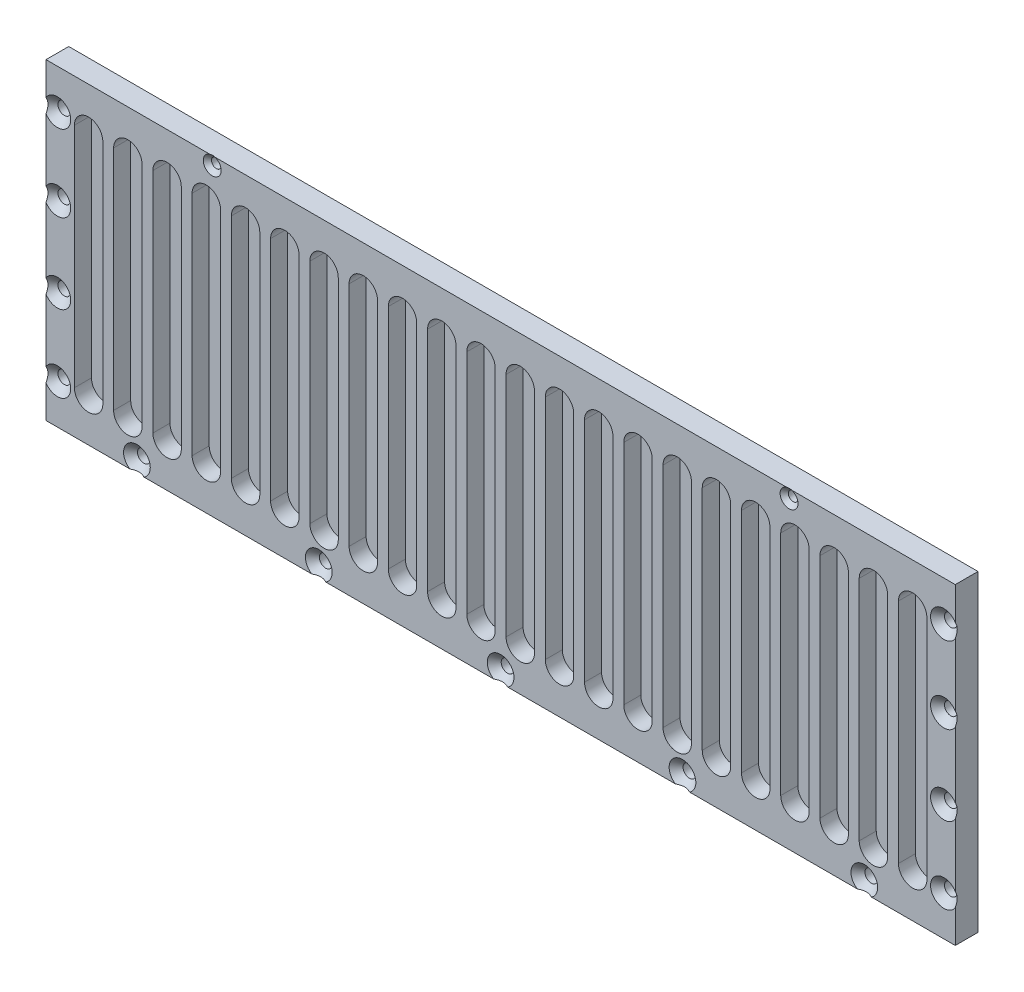
SolidWorks part; units mm, degrees
material "7079 Alloy"
ref_plane "Front Plane" through (0, 0, 0) normal (0, 0, 1) x (1, 0, 0)
ref_plane "Top Plane" through (0, 0, 0) normal (0, 1, 0) x (1, 0, 0)
ref_plane "Right Plane" through (0, 0, 0) normal (1, 0, 0) x (0, 0, -1)
sketch "Sketch1" plane through (0, 0, 0) normal (0, 0, 1) x (1, 0, 0)
  line L0 (-160, 0) -> (0, 0) construction
  line L1 (-160, 55) -> (160, 55)
  line L2 (-160, 55) -> (-160, -55)
  line L3 (-160, -55) -> (160, -55)
  line L4 (160, 55) -> (160, -55)
  line L5 (0, 0) -> (0, 55) construction
  dimension "D1" = 110
  dimension "D2" = 320
extrude "Extrude1" add sketch "Sketch1" along normal blind 8
sketch "Sketch2" plane through (0, 0, 8) normal (0, 0, 1) x (1, 0, 0)
  line L0 (156, 55) -> (156, -55) construction
  line L1 (160, 55) -> (-160, 55) construction
  line L2 (-160, -55) -> (160, -55) construction
  line L3 (0, 55) -> (0, -55) construction
  line L4 (160, 0) -> (0, 0) construction
  line L5 (160, -55) -> (160, 55) construction
  circle A0 centre (156, 41) radius 1.75
  circle A1 centre (156, 14) radius 1.75
  circle A2 centre (156, -14) radius 1.75
  circle A3 centre (156, -41) radius 1.75
  circle A4 centre (-156, -41) radius 1.75
  circle A5 centre (-156, -14) radius 1.75
  circle A6 centre (-156, 41) radius 1.75
  circle A7 centre (-156, 14) radius 1.75
  dimension "D1" = 3.5
  dimension "D2" = 14
  dimension "D3" = 27
  dimension "D4" = 4
extrude "Cut-Extrude1" cut sketch "Sketch2" against normal through all
sketch "Sketch5" plane through (0, 0, 8) normal (0, 0, 1) x (1, 0, 0)
  line L0 (145, 0) -> (145, 55) construction
  line L1 (-160, 55) -> (-160, -55) construction
  line L2 (145, 0) -> (160, 0) construction
  line L3 (160, -55) -> (160, 55) construction
  line L4 (150, 40) -> (150, -40)
  line L5 (140, 40) -> (140, -40)
  line L7 (160, 55) -> (-160, 55) construction
  line L37 (136.1905, 40) -> (136.1905, -40)
  line L38 (126.1905, 40) -> (126.1905, -40)
  line L39 (122.381, 40) -> (122.381, -40)
  line L40 (112.381, 40) -> (112.381, -40)
  line L41 (108.5714, 40) -> (108.5714, -40)
  line L42 (98.5714, 40) -> (98.5714, -40)
  line L43 (94.7619, 40) -> (94.7619, -40)
  line L44 (84.7619, 40) -> (84.7619, -40)
  line L45 (80.9524, 40) -> (80.9524, -40)
  line L46 (70.9524, 40) -> (70.9524, -40)
  line L47 (67.1429, 40) -> (67.1429, -40)
  line L48 (57.1429, 40) -> (57.1429, -40)
  line L49 (53.3333, 40) -> (53.3333, -40)
  line L50 (43.3333, 40) -> (43.3333, -40)
  line L51 (39.5238, 40) -> (39.5238, -40)
  line L52 (29.5238, 40) -> (29.5238, -40)
  line L53 (25.7143, 40) -> (25.7143, -40)
  line L54 (15.7143, 40) -> (15.7143, -40)
  line L55 (11.9048, 40) -> (11.9048, -40)
  line L56 (1.9048, 40) -> (1.9048, -40)
  line L57 (-1.9048, 40) -> (-1.9048, -40)
  line L58 (-11.9048, 40) -> (-11.9048, -40)
  line L59 (-15.7143, 40) -> (-15.7143, -40)
  line L60 (-25.7143, 40) -> (-25.7143, -40)
  line L61 (-29.5238, 40) -> (-29.5238, -40)
  line L62 (-39.5238, 40) -> (-39.5238, -40)
  line L63 (-43.3333, 40) -> (-43.3333, -40)
  line L64 (-53.3333, 40) -> (-53.3333, -40)
  line L65 (-57.1429, 40) -> (-57.1429, -40)
  line L66 (-67.1429, 40) -> (-67.1429, -40)
  line L67 (-70.9524, 40) -> (-70.9524, -40)
  line L68 (-80.9524, 40) -> (-80.9524, -40)
  line L69 (-84.7619, 40) -> (-84.7619, -40)
  line L70 (-94.7619, 40) -> (-94.7619, -40)
  line L71 (-98.5714, 40) -> (-98.5714, -40)
  line L72 (-108.5714, 40) -> (-108.5714, -40)
  line L93 (-112.381, 40) -> (-112.381, -40)
  line L94 (-122.381, 40) -> (-122.381, -40)
  line L95 (-126.1905, 40) -> (-126.1905, -40)
  line L96 (-136.1905, 40) -> (-136.1905, -40)
  line L97 (-140, 40) -> (-140, -40)
  line L98 (-150, 40) -> (-150, -40)
  arc A0 (150, 40) -> (140, 40) centre (145, 40) ccw
  arc A1 (150, -40) -> (140, -40) centre (145, -40) cw
  arc A30 (136.1905, 40) -> (126.1905, 40) centre (131.1905, 40) ccw
  arc A31 (136.1905, -40) -> (126.1905, -40) centre (131.1905, -40) cw
  arc A32 (122.381, 40) -> (112.381, 40) centre (117.381, 40) ccw
  arc A33 (122.381, -40) -> (112.381, -40) centre (117.381, -40) cw
  arc A34 (108.5714, 40) -> (98.5714, 40) centre (103.5714, 40) ccw
  arc A35 (108.5714, -40) -> (98.5714, -40) centre (103.5714, -40) cw
  arc A36 (94.7619, 40) -> (84.7619, 40) centre (89.7619, 40) ccw
  arc A37 (94.7619, -40) -> (84.7619, -40) centre (89.7619, -40) cw
  arc A38 (80.9524, 40) -> (70.9524, 40) centre (75.9524, 40) ccw
  arc A39 (80.9524, -40) -> (70.9524, -40) centre (75.9524, -40) cw
  arc A40 (67.1429, 40) -> (57.1429, 40) centre (62.1429, 40) ccw
  arc A41 (67.1429, -40) -> (57.1429, -40) centre (62.1429, -40) cw
  arc A42 (53.3333, 40) -> (43.3333, 40) centre (48.3333, 40) ccw
  arc A43 (53.3333, -40) -> (43.3333, -40) centre (48.3333, -40) cw
  arc A44 (39.5238, 40) -> (29.5238, 40) centre (34.5238, 40) ccw
  arc A45 (39.5238, -40) -> (29.5238, -40) centre (34.5238, -40) cw
  arc A46 (25.7143, 40) -> (15.7143, 40) centre (20.7143, 40) ccw
  arc A47 (25.7143, -40) -> (15.7143, -40) centre (20.7143, -40) cw
  arc A48 (11.9048, 40) -> (1.9048, 40) centre (6.9048, 40) ccw
  arc A49 (11.9048, -40) -> (1.9048, -40) centre (6.9048, -40) cw
  arc A50 (-1.9048, 40) -> (-11.9048, 40) centre (-6.9048, 40) ccw
  arc A51 (-1.9048, -40) -> (-11.9048, -40) centre (-6.9048, -40) cw
  arc A52 (-15.7143, 40) -> (-25.7143, 40) centre (-20.7143, 40) ccw
  arc A53 (-15.7143, -40) -> (-25.7143, -40) centre (-20.7143, -40) cw
  arc A54 (-29.5238, 40) -> (-39.5238, 40) centre (-34.5238, 40) ccw
  arc A55 (-29.5238, -40) -> (-39.5238, -40) centre (-34.5238, -40) cw
  arc A56 (-43.3333, 40) -> (-53.3333, 40) centre (-48.3333, 40) ccw
  arc A57 (-43.3333, -40) -> (-53.3333, -40) centre (-48.3333, -40) cw
  arc A58 (-57.1429, 40) -> (-67.1429, 40) centre (-62.1429, 40) ccw
  arc A59 (-57.1429, -40) -> (-67.1429, -40) centre (-62.1429, -40) cw
  arc A60 (-70.9524, 40) -> (-80.9524, 40) centre (-75.9524, 40) ccw
  arc A61 (-70.9524, -40) -> (-80.9524, -40) centre (-75.9524, -40) cw
  arc A62 (-84.7619, 40) -> (-94.7619, 40) centre (-89.7619, 40) ccw
  arc A63 (-84.7619, -40) -> (-94.7619, -40) centre (-89.7619, -40) cw
  arc A64 (-98.5714, 40) -> (-108.5714, 40) centre (-103.5714, 40) ccw
  arc A65 (-98.5714, -40) -> (-108.5714, -40) centre (-103.5714, -40) cw
  arc A66 (-112.381, 40) -> (-122.381, 40) centre (-117.381, 40) ccw
  arc A67 (-112.381, -40) -> (-122.381, -40) centre (-117.381, -40) cw
  arc A90 (-126.1905, 40) -> (-136.1905, 40) centre (-131.1905, 40) ccw
  arc A91 (-126.1905, -40) -> (-136.1905, -40) centre (-131.1905, -40) cw
  arc A92 (-140, 40) -> (-150, 40) centre (-145, 40) ccw
  arc A93 (-140, -40) -> (-150, -40) centre (-145, -40) cw
  point P11 (150, 0)
  point P16 (140, 0)
  dimension "D1" = 80
  dimension "D2" = 5
  dimension "D3" = 15
  dimension "D5" = 15
  dimension "D4" = 22
extrude "Cut-Extrude2" cut sketch "Sketch5" against normal blind 6
sketch "Sketch6" plane through (0, 0, 8) normal (0, 0, 1) x (1, 0, 0)
  line L0 (-152, -55) -> (-152, -51) construction
  line L1 (-160, -55) -> (160, -55) construction
  line L2 (-152, -51) -> (0, -51) construction
  line L3 (0, -51) -> (0, -55) construction
  line L4 (-160, 55) -> (-160, -55) construction
  circle A0 centre (-64, -51) radius 2.25
  circle A1 centre (0, -51) radius 2.25
  circle A2 centre (64, -51) radius 2.25
  circle A3 centre (-128, -51) radius 2.25
  circle A4 centre (128, -51) radius 2.25
  dimension "D2" = 5
  dimension "D3" = 4.5
  dimension "D4" = 8
  dimension "D5" = 4
  dimension "D1" = 64
extrude "Cut-Extrude3" cut sketch "Sketch6" against normal blind 10
sketch "Sketch9" plane through (0, 0, 8) normal (0, 0, 1) x (1, 0, 0)
  line L0 (160, 52) -> (101.5, 52) construction
  line L1 (160, -55) -> (160, 55) construction
  line L2 (101.5, 52) -> (101.5, 55) construction
  line L3 (160, 55) -> (-160, 55) construction
  line L4 (0, 0) -> (0, 55) construction
  circle A0 centre (101.5, 52) radius 1.5
  circle A1 centre (-101.5, 52) radius 1.5
  dimension "D1" = 3
  dimension "D2" = 3
  dimension "D3" = 58.5
extrude "Cut-Extrude4" cut sketch "Sketch9" against normal blind 10
hole_wizard "CSK for M4 Flat Head Machine Screw1" positions "Sketch4" profile "Sketch3" countersink size "M4" standard "Ansi Metric" end condition through all
sketch "Sketch4" plane through (0, 0, 8) normal (0, 0, 1) x (1, 0, 0)
  point P1 (156, 41)
  point P4 (156, 14)
  point P7 (156, -14)
  point P10 (156, -41)
  point P13 (-156, -41)
  point P16 (-156, -14)
  point P19 (-156, 14)
  point P26 (-156, 41)
  point P35 (-128, -51)
  point P38 (-64, -51)
  point P41 (0, -51)
  point P44 (64, -51)
  point P47 (128, -51)
sketch "Sketch3" plane through (156, 41, 8) normal (1, 0, 0) x (0, -1, 0)
  line L0 (0, 0) -> (0, 8)
  line L1 (0, 8) -> (2.25, 8)
  line L2 (2.25, 8) -> (2.25, 2.45)
  line L3 (2.25, 2.45) -> (4.7, 0)
  line L5 (4.7, 0) -> (0, 0)
  line L6 (-2.25, 2.45) -> (-4.7, 0) construction
  line L11 (0, -6.35) -> (0, 107.95) construction
  dimension "Thru Hole Dia." = 4.5
  dimension "Thru Hole Depth" = 8
  dimension "Near C'Sink Dia." = 9.4
  dimension "Near C'Sink Angle" = 90
hole_wizard "CSK for M3 Flat Head Machine Screw1" positions "Sketch11" profile "Sketch10" countersink size "M3" standard "Ansi Metric" end condition through all
sketch "Sketch11" plane through (0, 0, 8) normal (0, 0, 1) x (1, 0, 0)
  point P1 (-101.5, 52)
  point P4 (101.5, 52)
sketch "Sketch10" plane through (-101.5, 52, 8) normal (1, 0, 0) x (0, -1, 0)
  line L0 (0, 0) -> (0, 8)
  line L1 (0, 8) -> (1.7, 8)
  line L2 (1.7, 8) -> (1.7, 1.45)
  line L3 (1.7, 1.45) -> (3.15, 0)
  line L5 (3.15, 0) -> (0, 0)
  line L6 (-1.7, 1.45) -> (-3.15, 0) construction
  line L11 (0, -6.35) -> (0, 107.95) construction
  dimension "Thru Hole Dia." = 3.4
  dimension "Thru Hole Depth" = 8
  dimension "Near C'Sink Dia." = 6.3
  dimension "Near C'Sink Angle" = 90
